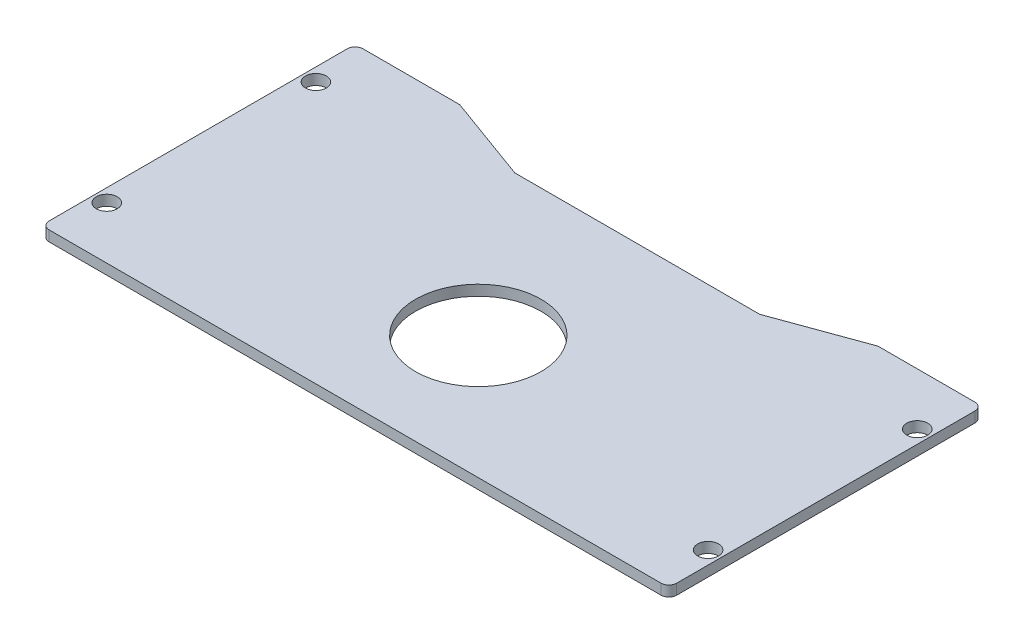
SolidWorks part; units mm, degrees
ref_plane "前视基准面" through (0, 0, 0) normal (0, 0, 1) x (1, 0, 0)
ref_plane "上视基准面" through (0, 0, 0) normal (0, 1, 0) x (1, 0, 0)
ref_plane "右视基准面" through (0, 0, 0) normal (1, 0, 0) x (0, 0, -1)
other "Configuration Table"
sketch "草图1" plane through (0, 0, 0) normal (0, 1, 0) x (1, 0, 0)
  line L0 (0, 30) -> (120, 30) construction
  line L1 (0, 0) -> (120, 0)
  line L2 (0, 0) -> (0, 60)
  line L3 (0, 60) -> (120, 60)
  line L4 (120, 0) -> (120, 60)
  line L6 (60, 60) -> (60, 0) construction
  dimension "D1" = 120
  dimension "D2" = 60
extrude "凸台-拉伸1" add sketch "草图1" along normal blind 2
sketch "草图2" plane through (0, 2, 0) normal (0, 1, 0) x (1, 0, 0)
  line L0 (120, 30) -> (0, 30) construction
  line L1 (120, 0) -> (120, 60) construction
  line L2 (0, 60) -> (0, 0) construction
  line L3 (117.5, 60) -> (117.5, 0) construction
  line L4 (120, 60) -> (0, 60) construction
  line L5 (60, 60) -> (60, 0) construction
  line L6 (0, 0) -> (120, 0) construction
  circle A0 centre (117.5, 50) radius 2
  circle A1 centre (117.5, 10) radius 2
  circle A2 centre (2.5, 50) radius 2
  circle A3 centre (2.5, 10) radius 2
  dimension "D2" = 4
  dimension "D1" = 2.5
  dimension "D3" = 20
extrude "切除-拉伸1" cut sketch "草图2" against normal up to surface (2 mm away) up to face at (60, 0, -30)
sketch "草图3" plane through (0, 2, 0) normal (0, 1, 0) x (1, 0, 0)
  line L0 (20, 60) -> (36.5824, 53.9645)
  line L1 (120, 60) -> (0, 60) construction
  line L2 (60, 60) -> (60, 0) construction
  line L3 (0, 0) -> (120, 0) construction
  line L4 (36.5824, 53.9645) -> (83.4176, 53.9645)
  line L5 (100, 60) -> (83.4176, 53.9645)
  line L6 (20, 60) -> (100, 60)
  circle A0 centre (60, 23.5563) radius 12
  point P13 (60, 53.9645)
  dimension "D1" = 24
  dimension "D2" = 40
  dimension "D3" = 20
  dimension "D4" = 23.4176
extrude "切除-拉伸2" cut sketch "草图3" against normal up to surface (2 mm away) up to face at (117.5, 0, -12)
fillet "圆角1" radius 1.5 4 edges at (120, 1, 0) (120, 1, -60) (0, 1, 0) (0, 1, -60)
